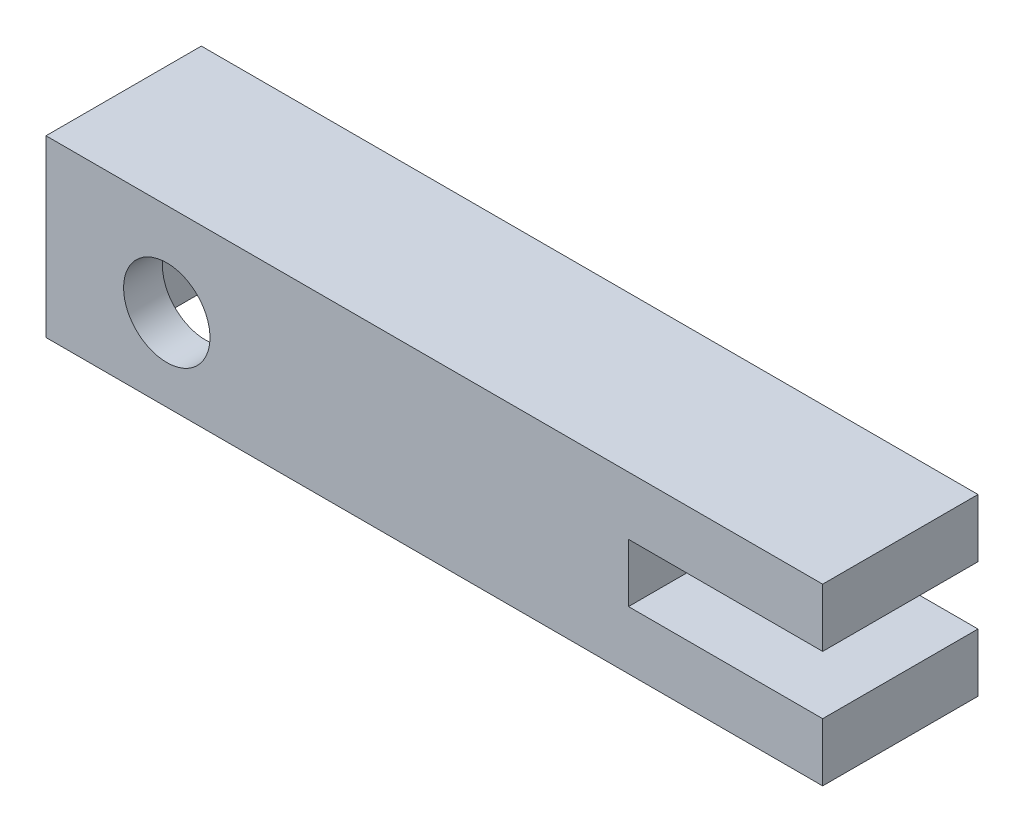
SolidWorks part; units mm, degrees
ref_plane "Alzado" through (0, 0, 0) normal (0, 0, 1) x (1, 0, 0)
ref_plane "Planta" through (0, 0, 0) normal (0, 1, 0) x (1, 0, 0)
ref_plane "Vista lateral" through (0, 0, 0) normal (1, 0, 0) x (0, 0, -1)
sketch "Croquis1" plane through (0, 0, 0) normal (0, 1, 0) x (1, 0, 0)
  line L1 (-175, -20) -> (175, -20)
  line L2 (-175, -20) -> (-175, 20)
  line L3 (-175, 20) -> (175, 20)
  line L4 (175, -20) -> (175, 20)
  line L5 (-175, -20) -> (175, 20) construction
  line L6 (-175, 20) -> (175, -20) construction
  point P0 (0, 0)
  dimension "D1" = 350
  dimension "D2" = 40
extrude "Saliente-Extruir1" add sketch "Croquis1" along normal blind 45
sketch "Croquis2" plane through (0, 0, -20) normal (0, 0, -1) x (-1, 0, 0)
  line L0 (-175, 0) -> (175, 0) construction
  line L1 (-165, 0) -> (-122.8, 0)
  line L2 (-165, 0) -> (-165, 42.2)
  line L3 (-165, 42.2) -> (-122.8, 42.2)
  line L4 (-122.8, 0) -> (-122.8, 42.2)
  line L5 (-175, 45) -> (-175, 0) construction
  dimension "D1" = 10
  dimension "D2" = 42.2
  dimension "D3" = 42.2
extrude "Cortar-Extruir1" cut sketch "Croquis2" against normal blind 30
sketch "Croquis3" plane through (0, 0, 10) normal (0, 0, -1) x (-1, 0, 0)
  line L0 (-165, 42.2) -> (-122.8, 0) construction
  line L4 (-165, 42.2) -> (-165, 0)
  line L5 (-165, 0) -> (-122.8, 0)
  line L6 (-122.8, 0) -> (-122.8, 42.2)
  line L7 (-122.8, 42.2) -> (-165, 42.2)
  line L8 (-165, 42.2) -> (-165, 0)
  line L9 (-165, 0) -> (-122.8, 0)
  line L10 (-122.8, 0) -> (-122.8, 42.2)
  line L11 (-122.8, 42.2) -> (-165, 42.2)
  circle A0 centre (-143.9, 21.1) radius 11.125
  dimension "D2" = 22.25
  dimension "D1" = 0
extrude "Cortar-Extruir2" cut sketch "Croquis3" against normal blind 30 contours A0
mirror "Simetría1" about plane through (0, 0, 0) normal (1, 0, 0) of "Cortar-Extruir2", "Cortar-Extruir1"
sketch "Croquis4" plane through (0, 0, 20) normal (0, 0, 1) x (1, 0, 0)
  line L1 (25, 0) -> (25, 15)
  line L2 (-175, 0) -> (175, 0) construction
  line L3 (25, 15) -> (-25, 15)
  line L4 (-25, 15) -> (-25, 30)
  line L5 (-25, 30) -> (25, 30)
  line L6 (25, 30) -> (25, 45)
  line L7 (-175, 45) -> (175, 45) construction
  line L12 (-175, 0) -> (175, 0)
  line L13 (175, 0) -> (175, 45)
  line L14 (175, 45) -> (-175, 45)
  line L15 (-175, 45) -> (-175, 0)
  line L16 (-175, 0) -> (175, 0)
  line L17 (175, 0) -> (175, 45)
  line L18 (175, 45) -> (-175, 45)
  line L19 (-175, 45) -> (-175, 0)
  circle M9 centre (143.9, 21.1) radius 11.125
  line M10 (-175, 0) -> (175, 0)
  line M11 (175, 0) -> (175, 45)
  line M12 (175, 45) -> (-175, 45)
  dimension "D1" = 0
  dimension "D2" = 50
  dimension "D3" = 25
  dimension "D4" = 15
  dimension "D5" = 15
  dimension "D6" = 25
extrude "Cortar-Extruir3" cut sketch "Croquis4" against normal through all contours L6 L5 L4 L3 L1 M10 M11 M12 M9
